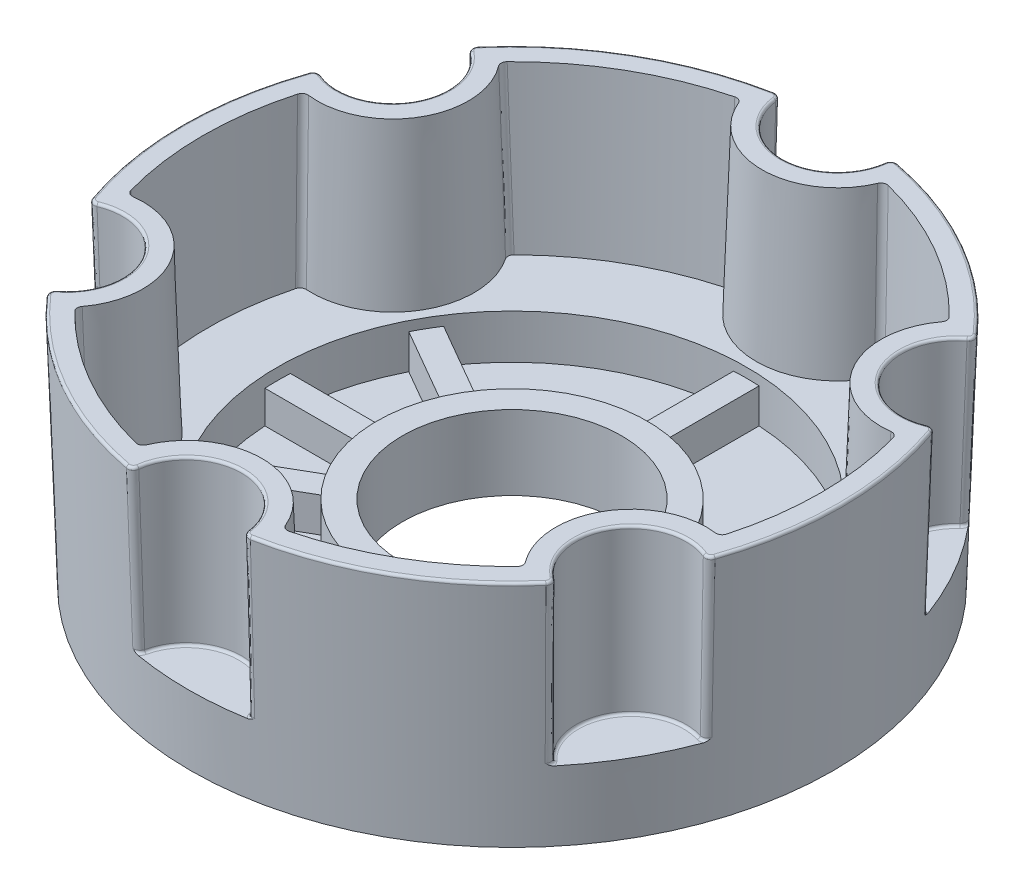
SolidWorks part; units mm, degrees
ref_plane "Alzado" through (0, 0, 0) normal (0, 0, 1) x (1, 0, 0)
ref_plane "Planta" through (0, 0, 0) normal (0, 1, 0) x (1, 0, 0)
ref_plane "Vista lateral" through (0, 0, 0) normal (1, 0, 0) x (0, 0, -1)
sketch "Croquis1" plane through (0, 0, 0) normal (0, 1, 0) x (1, 0, 0)
  circle A0 centre (0, 0) radius 31.5
  dimension "D1" = 63
extrude "Saliente-Extruir1" add sketch "Croquis1" along normal blind 23 draft 2 draft outward yes
sketch "Croquis2" plane through (0, 23, 0) normal (0, 1, 0) x (1, 0, 0)
  line L0 (0, 0) -> (32.3032, 0) construction
  line L1 (0, 0) -> (0, 32.3032) construction
  line L2 (0, 32.3032) -> (0, 31.9079) construction
  line L3 (0, 24.5) -> (7.4079, 24.5) construction
  line L4 (7.4079, 24.5) -> (7.4079, 31.9079) construction
  line L5 (-7, 29.4836) -> (7, 29.4836) construction
  circle A0 centre (0, 0) radius 32.3032 construction
  circle A1 centre (0, 31.9079) radius 7.4079 construction
  circle A2 centre (0, 0) radius 30.3032 construction
  circle A3 centre (27.6331, 15.954) radius 7.4079 construction
  circle A4 centre (27.6331, -15.954) radius 7.4079 construction
  circle A5 centre (0, -31.9079) radius 7.4079 construction
  circle A6 centre (-27.6331, -15.954) radius 7.4079 construction
  circle A7 centre (-27.6331, 15.954) radius 7.4079 construction
  circle A8 centre (0, 31.9079) radius 5.4079
  circle A9 centre (27.6331, 15.954) radius 5.4079
  circle A10 centre (27.6331, -15.954) radius 5.4079
  circle A11 centre (0, -31.9079) radius 5.4079
  circle A12 centre (-27.6331, -15.954) radius 5.4079
  circle A13 centre (-27.6331, 15.954) radius 5.4079
  point P27 (0, 0)
  point P39 (0, 0)
  dimension "D1" = 24.5
  dimension "D2" = 2
  dimension "D5" = 2
  dimension "D3" = 14
  dimension "D4" = 6
  dimension "D6" = 6
extrude "Cortar-Extruir1" cut sketch "Croquis2" against normal blind 16
sketch "Croquis3" plane through (0, 0, 0) normal (0, -1, 0) x (1, 0, 0)
  circle A0 centre (0, 0) radius 10.75
  dimension "D1" = 21.5
extrude "Cortar-Extruir2" cut sketch "Croquis3" against normal blind 16
sketch "Croquis4" plane through (0, 23, 0) normal (0, 1, 0) x (1, 0, 0)
  line L0 (0, 0) -> (32.3032, 0) construction
  arc A13 (30.2844, -11.2406) -> (30.2844, 11.2406) centre (0, 0) ccw construction
  arc A25 (-7, 29.4836) -> (7, 29.4836) centre (0, 31.9079) ccw
  arc A26 (-7, 29.4836) -> (7, 29.4836) centre (0, 31.9079) ccw
  arc A27 (-7, 29.4836) -> (-22.0335, 20.804) centre (0, 0) ccw
  arc A28 (-7, 29.4836) -> (-22.0335, 20.804) centre (0, 0) ccw
  arc A29 (-29.0335, 8.6796) -> (-22.0335, 20.804) centre (-27.6331, 15.954) ccw
  arc A30 (-29.0335, 8.6796) -> (-22.0335, 20.804) centre (-27.6331, 15.954) ccw
  arc A31 (-29.0335, 8.6796) -> (-29.0335, -8.6796) centre (0, 0) ccw
  arc A32 (-29.0335, 8.6796) -> (-29.0335, -8.6796) centre (0, 0) ccw
  arc A33 (-22.0335, -20.804) -> (-29.0335, -8.6796) centre (-27.6331, -15.954) ccw
  arc A34 (-22.0335, -20.804) -> (-29.0335, -8.6796) centre (-27.6331, -15.954) ccw
  arc A35 (-22.0335, -20.804) -> (-7, -29.4836) centre (0, 0) ccw
  arc A36 (-22.0335, -20.804) -> (-7, -29.4836) centre (0, 0) ccw
  arc A49 (7, -29.4836) -> (-7, -29.4836) centre (0, -31.9079) ccw
  arc A50 (7, -29.4836) -> (-7, -29.4836) centre (0, -31.9079) ccw
  arc A51 (7, -29.4836) -> (22.0335, -20.804) centre (0, 0) ccw
  arc A52 (7, -29.4836) -> (22.0335, -20.804) centre (0, 0) ccw
  arc A53 (29.0335, -8.6796) -> (22.0335, -20.804) centre (27.6331, -15.954) ccw
  arc A54 (29.0335, -8.6796) -> (22.0335, -20.804) centre (27.6331, -15.954) ccw
  arc A55 (29.0335, -8.6796) -> (29.0335, 8.6796) centre (0, 0) ccw
  arc A56 (29.0335, -8.6796) -> (29.0335, 8.6796) centre (0, 0) ccw
  arc A57 (22.0335, 20.804) -> (29.0335, 8.6796) centre (27.6331, 15.954) ccw
  arc A58 (22.0335, 20.804) -> (29.0335, 8.6796) centre (27.6331, 15.954) ccw
  arc A59 (22.0335, 20.804) -> (7, 29.4836) centre (0, 0) ccw
  arc A60 (22.0335, 20.804) -> (7, 29.4836) centre (0, 0) ccw
  dimension "D1" = 2
extrude "Cortar-Extruir3" cut sketch "Croquis4" against normal blind 16 draft 2
sketch "Croquis6" plane through (0, 7, 0) normal (0, 1, 0) x (1, 0, 0)
  circle A0 centre (0, 0) radius 13.25
  circle A1 centre (0, 0) radius 23
  dimension "D1" = 26.5
  dimension "D2" = 46
extrude "Cortar-Extruir4" cut sketch "Croquis6" against normal blind 4.35
sketch "Croquis8" plane through (0, 2.65, 0) normal (0, 1, 0) x (1, 0, 0)
  line L0 (0, 0) -> (30.3032, 0) construction
  line L1 (21.2176, 12.25) -> (0, 0) construction
  line L2 (0, 23.9413) -> (0, 0) construction
  line L3 (20.5926, 13.3325) -> (1.25, 2.1651)
  line L4 (1.25, 23.9413) -> (1.25, 2.1651)
  line L5 (21.8426, 11.1675) -> (-1.25, -2.1651)
  line L6 (-1.25, 23.9413) -> (-1.25, -2.1651)
  line L7 (20.1087, -13.0532) -> (1.25, -2.1651)
  line L8 (21.3587, -10.8881) -> (-1.25, 2.1651)
  line L9 (1.25, -24.5) -> (1.25, -2.1651)
  line L10 (-1.25, -24.5) -> (-1.25, 2.1651)
  line L11 (-21.3587, -10.8881) -> (-2.5, 0)
  line L12 (-20.1087, -13.0532) -> (2.5, 0)
  line L13 (-21.8426, 11.1675) -> (-2.5, 0)
  line L14 (-20.5926, 13.3325) -> (2.5, 0)
  arc A0 (29.0335, -8.6796) -> (29.0335, 8.6796) centre (0, 0) ccw construction
  circle A1 centre (0, 0) radius 23
  circle A2 centre (0, 0) radius 13.25
  circle A3 centre (0, 0) radius 13.25 construction
  circle A4 centre (0, 0) radius 23 construction
  arc A5 (22.0335, 20.804) -> (29.0335, 8.6796) centre (27.6331, 15.954) ccw construction
  arc A6 (-7.3452, 28.8232) -> (7.3452, 28.8232) centre (0, 31.9079) ccw construction
  point P40 (0, 0)
  circle M3 centre (0, 0) radius 13.25
  circle M4 centre (0, 0) radius 23
  dimension "D1" = 1.25
  dimension "D2" = 1.25
  dimension "D3" = 3
extrude "Saliente-Extruir2" add sketch "Croquis8" along normal blind 3.4 contours L14 L13 M4 M3 | L6 L4 M4 M3 | L5 L3 M4 M3 | L8 L7 M4 M3 | L10 L9 M4 M3 | L12 L11 M4 M3
sketch "Croquis9" plane through (0, 2.65, 0) normal (0, 1, 0) x (1, 0, 0)
  line L0 (0, 0) -> (23, 0) construction
  line L1 (0, -1.25) -> (23, -1.25)
  line L2 (0, 1.25) -> (23, 1.25)
  arc A0 (20.5141, -10.4005) -> (20.5141, 10.4005) centre (0, 0) ccw construction
  circle A1 centre (0, 0) radius 23
  circle A2 centre (0, 0) radius 13.25
  circle A3 centre (0, 0) radius 13.25 construction
  arc M2 (12.0487, 5.5129) -> (12.0487, -5.5129) centre (0, 0) cw
  arc M4 (20.5141, -10.4005) -> (20.5141, 10.4005) centre (0, 0) ccw
  dimension "D1" = 1.25
  dimension "D2" = 1.25
extrude "Saliente-Extruir3" add sketch "Croquis9" along normal blind 3.2 contours L0 A1 L2 M2 | L0 A2 L1 M4
pattern_circular "MatrizC3" count 4 over 360 about axis through (0, 16, 0) along (0, -1, 0) of "Saliente-Extruir3"
sketch "Croquis10" plane through (0, 7, 0) normal (0, 1, 0) x (1, 0, 0)
  circle A0 centre (0, 0) radius 10.75
  circle A1 centre (0, 0) radius 13.25
  circle A2 centre (0, 0) radius 13.25 construction
  circle A3 centre (0, 0) radius 10.75 construction
extrude "Saliente-Extruir4" add sketch "Croquis10" along normal blind 0.3
fillet "Redondeo4" radius 0.6 24 edges at (-5.3902, 12.271, -31.4702) (5.4023, 17.729, -31.6615) (-29.9491, 12.271, -11.0671) (-24.7185, 17.729, -20.5093) (-24.5589, 12.271, 20.4032) (-30.1208, 17.729, 11.1522) (5.3902, 12.271, 31.4702) (-5.4023, 17.729, 31.6615) (29.9491, 12.271, 11.0671) (24.7185, 17.729, 20.5093) (24.5589, 12.271, -20.4032) (30.1208, 17.729, -11.1522)
fillet "Redondeo6" radius 0.25 24 edges at (-5.5419, 23, -31.57) (0, 23, -26.5) (5.6785, 23, -31.6689) (16.1516, 23, -27.9754) (24.5695, 23, -20.5845) (22.9497, 23, -13.25) (30.2653, 23, -10.9167) (32.3032, 23, 0) (30.1114, 23, 10.9855) (22.9497, 23, 13.25) (24.5868, 23, 20.7522) (16.1516, 23, 27.9754) (5.5419, 23, 31.57) (0, 23, 26.5) (-5.6785, 23, 31.6689) (-16.1516, 23, 27.9754) (-24.5695, 23, 20.5845) (-22.9497, 23, 13.25) (-30.2653, 23, 10.9167) (-32.3032, 23, 0) (-30.1114, 23, -10.9855) (-22.9497, 23, -13.25) (-24.5868, 23, -20.7522) (-16.1516, 23, -27.9754)
fillet "Redondeo7" radius 0.25 18 edges at (5.5814, 7, 31.1187) (-5.4866, 7, 31.0566) (-24.1589, 7, 20.3929) (-29.6391, 7, 10.7768) (-29.7402, 7, -10.7257) (-24.1525, 7, -20.2798) (-5.5814, 7, -31.1187) (5.4866, 7, -31.0566) (24.1589, 7, -20.3929) (29.6391, 7, -10.7768) (29.7402, 7, 10.7257) (24.1525, 7, 20.2798) (0, 7, 26.5) (-22.9497, 7, 13.25) (-22.9497, 7, -13.25) (0, 7, -26.5) (22.9497, 7, -13.25) (22.9497, 7, 13.25)
sketch "Croquis11" plane through (0, 7, 0) normal (0, 1, 0) x (1, 0, 0)
  line L0 (0, 0) -> (23.8125, 0) construction
  circle A0 centre (23.8125, 0) radius 1
  dimension "D2" = 2
  dimension "D1" = 23.8125
extrude "Cortar-Extruir5" cut sketch "Croquis11" against normal blind 1
